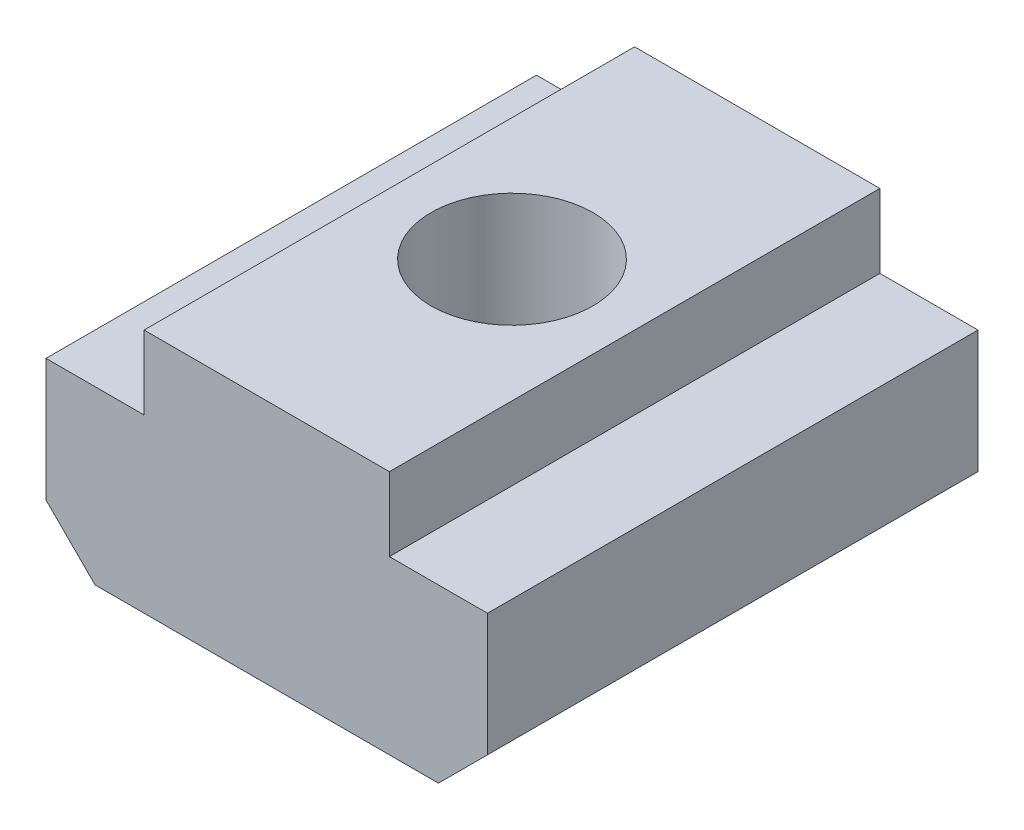
SolidWorks part; units mm, degrees
ref_plane "Front Plane" through (0, 0, 0) normal (0, 0, 1) x (1, 0, 0)
ref_plane "Top Plane" through (0, 0, 0) normal (0, 1, 0) x (1, 0, 0)
ref_plane "Right Plane" through (0, 0, 0) normal (1, 0, 0) x (0, 0, -1)
sketch "Sketch1" plane through (0, 0, 0) normal (0, 0, 1) x (1, 0, 0)
  line L0 (0, 0) -> (0, 46.9655) construction
  line L1 (-3.5, 0) -> (3.5, 0)
  line L2 (3.5, 0) -> (4.5, 1)
  line L3 (4.5, 1) -> (4.5, 3.5)
  line L4 (4.5, 3.5) -> (2.5, 3.5)
  line L5 (2.5, 3.5) -> (2.5, 5)
  line L6 (2.5, 5) -> (-2.5, 5)
  line L7 (-2.5, 5) -> (-2.5, 3.5)
  line L8 (-2.5, 3.5) -> (-4.5, 3.5)
  line L9 (-4.5, 3.5) -> (-4.5, 1)
  line L10 (-4.5, 1) -> (-3.5, 0)
  point P10 (0, 5)
  point P14 (-4.5, 2.25)
  dimension "D1" = 5
  dimension "D2" = 9
  dimension "D3" = 4.5
  dimension "D4" = 1.5
  dimension "D5" = 5
  dimension "D6" = 1
  dimension "D7" = 1
  dimension "D8" = 1
extrude "Boss-Extrude1" add sketch "Sketch1" along normal blind 10
sketch "Sketch2" plane through (0, 5, 0) normal (0, 1, 0) x (1, 0, 0)
  line L0 (-2.5, 0) -> (2.5, -10) construction
  point P4 (0, -5)
hole_wizard "M4x0.7 Tapped Hole1" positions "Sketch3" profile "Sketch4" tap size "M4x0.7" standard "ANSI Metric" end condition through all
sketch "Sketch3" plane through (0, 5, 0) normal (0, 1, 0) x (1, 0, 0)
  point P0 (0, -5)
sketch "Sketch4" plane through (0, 5, 5) normal (1, 0, 0) x (0, 0, 1)
  line L0 (0, 0) -> (0, 5)
  line L1 (0, 5) -> (1.65, 5)
  line L2 (1.65, 5) -> (1.65, 0)
  line L5 (1.65, 0) -> (0, 0)
  line L11 (0, -6.35) -> (0, 107.95) construction
  dimension "Thru Tap Drill Dia." = 3.3
  dimension "Thru Tap Drill Depth" = 5
cosmetic thread "Hole Thread1" parameters "D2"=4
